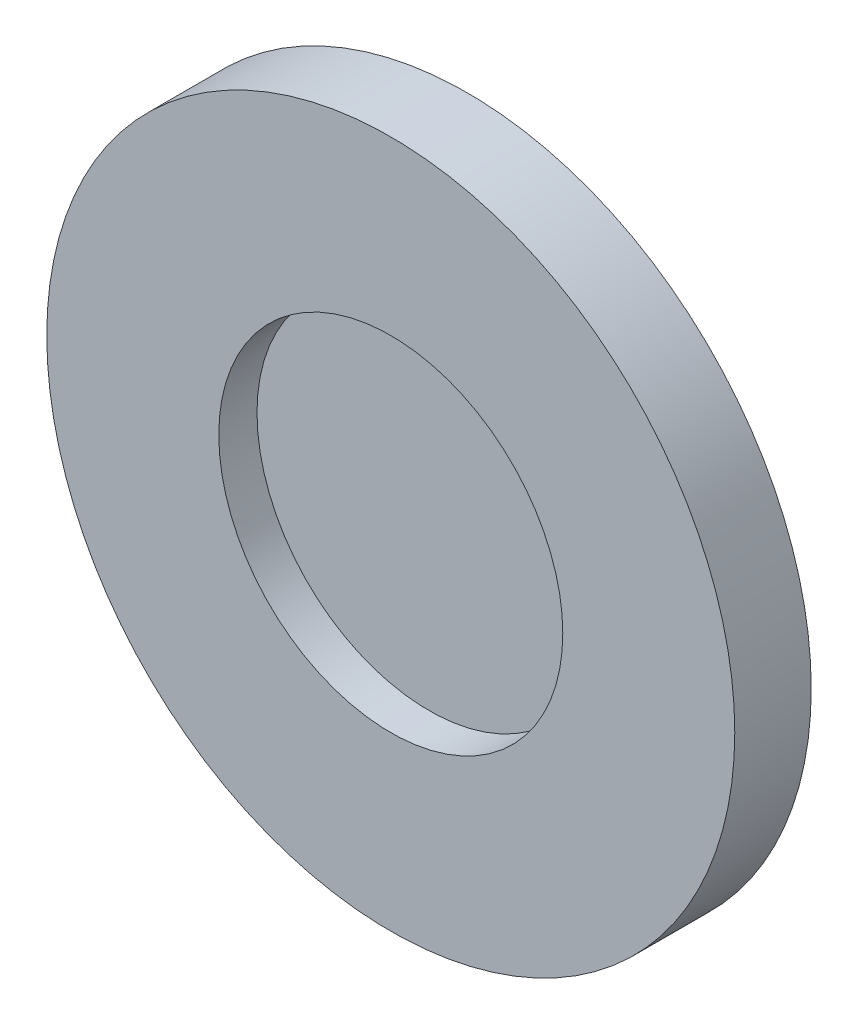
SolidWorks part; units mm, degrees
material "Kaucuk"
ref_plane "Ön Düzlem" through (0, 0, 0) normal (0, 0, 1) x (1, 0, 0)
ref_plane "Üst Düzlem" through (0, 0, 0) normal (0, 1, 0) x (1, 0, 0)
ref_plane "Sağ Düzlem" through (0, 0, 0) normal (1, 0, 0) x (0, 0, -1)
sketch "Çizim1" plane through (0, 0, 0) normal (0, 0, 1) x (1, 0, 0)
  circle A0 centre (0, 0) radius 90
  dimension "D1" = 180
extrude "Yükseklik-Ekstrüzyon1" add sketch "Çizim1" along normal blind 10
sketch "Çizim2" plane through (0, 0, 10) normal (0, 0, 1) x (1, 0, 0)
  circle A0 centre (0, 0) radius 90 construction
  circle A1 centre (0, 0) radius 90
  circle A2 centre (0, 0) radius 45
  dimension "D1" = 90
extrude "Yükseklik-Ekstrüzyon2" add sketch "Çizim2" along normal blind 10
